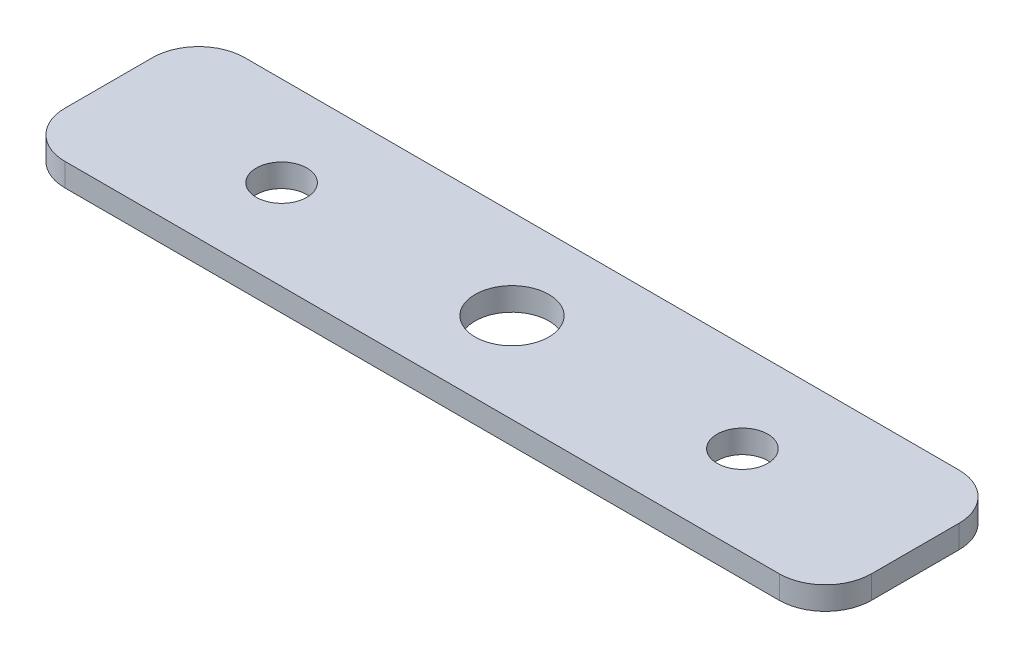
SolidWorks part; units mm, degrees
ref_plane "Alzado" through (0, 0, 0) normal (0, 0, 1) x (1, 0, 0)
ref_plane "Planta" through (0, 0, 0) normal (0, 1, 0) x (1, 0, 0)
ref_plane "Vista lateral" through (0, 0, 0) normal (1, 0, 0) x (0, 0, -1)
sketch "Croquis1" plane through (0, 0, 0) normal (0, 1, 0) x (1, 0, 0)
  line L1 (-35, -7.8) -> (35, -7.8)
  line L2 (-35, -7.8) -> (-35, 7.8)
  line L3 (-35, 7.8) -> (35, 7.8)
  line L4 (35, -7.8) -> (35, 7.8)
  line L5 (-35, -7.8) -> (35, 7.8) construction
  line L6 (-35, 7.8) -> (35, -7.8) construction
  point P0 (0, 0)
  dimension "D1" = 15.6
  dimension "D2" = 70
extrude "Saliente-Extruir1" add sketch "Croquis1" along normal blind 2
sketch "Croquis3" plane through (0, 0, 0) normal (0, 1, 0) x (1, 0, 0)
  line L0 (-1.1, 0) -> (1.1, 0) construction
  line L1 (0, -1.1) -> (0, 1.1) construction
  circle A0 centre (0, 0) radius 3.2
  circle A1 centre (20, 0) radius 2.2
  circle A2 centre (-20, 0) radius 2.2
  dimension "D1" = 6.4
  dimension "D2" = 4.4
  dimension "D3" = 40
extrude "Cortar-Extruir2" cut sketch "Croquis3" along normal through all both and the other way through all
fillet "Redondeo1" radius 4 4 edges at (35, 1, -7.8) (35, 1, 7.8) (-35, 1, 7.8) (-35, 1, -7.8)
